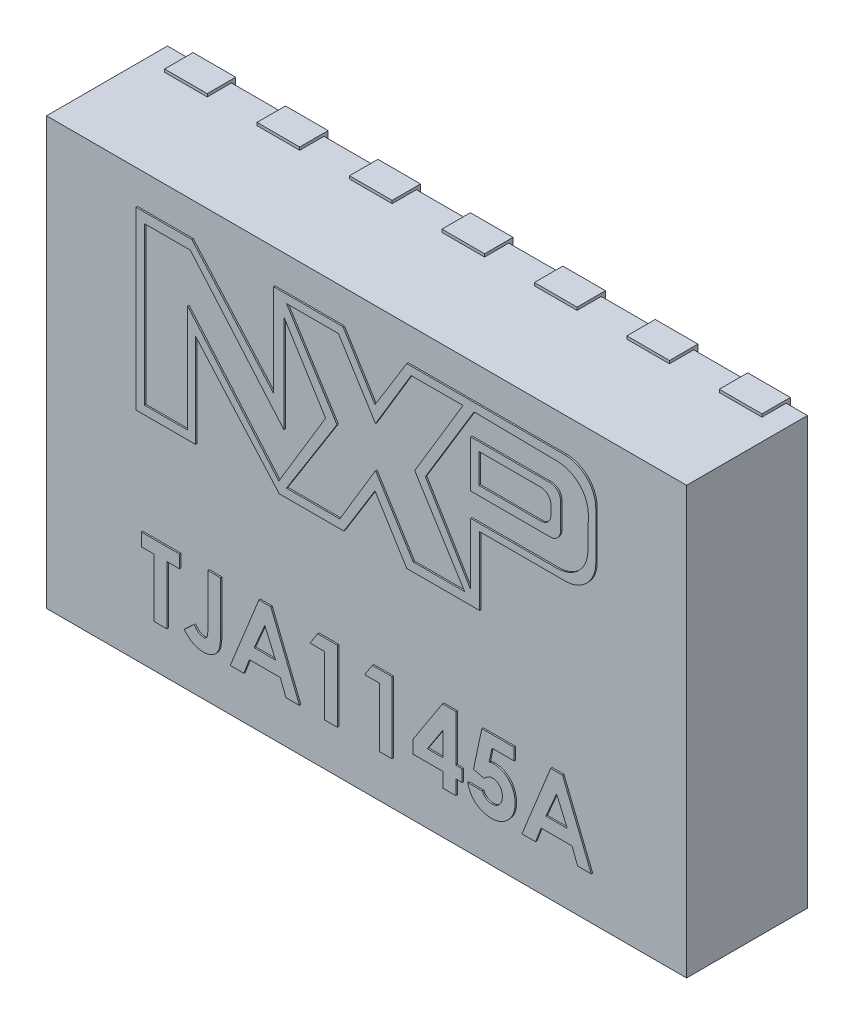
SolidWorks part; units mm, degrees
ref_plane "Front Plane" through (0, 0, 0) normal (0, 0, 1) x (1, 0, 0)
ref_plane "Top Plane" through (0, 0, 0) normal (0, 1, 0) x (1, 0, 0)
ref_plane "Right Plane" through (0, 0, 0) normal (1, 0, 0) x (0, 0, -1)
sketch "Sketch1" plane through (0, 0, 0) normal (0, 0, 1) x (1, 0, 0)
  line L1 (2.25, 1.5) -> (-2.25, 1.5)
  line L2 (2.25, 1.5) -> (2.25, -1.5)
  line L3 (2.25, -1.5) -> (-2.25, -1.5)
  line L4 (-2.25, 1.5) -> (-2.25, -1.5)
  line L5 (2.25, 1.5) -> (-2.25, -1.5) construction
  line L6 (2.25, -1.5) -> (-2.25, 1.5) construction
  point P0 (0, 0)
  dimension "D1" = 4.5
  dimension "D2" = 3
extrude "Boss-Extrude1" add sketch "Sketch1" along normal blind 0.85
sketch "Sketch2" plane through (0, 0, 0) normal (0, 0, -1) x (-1, 0, 0)
  line L0 (-2.25, 1.5) -> (2.25, 1.5) construction
  line L1 (2.1, 0.8) -> (-2.1, 0.8)
  line L2 (2.1, 0.8) -> (2.1, -0.8)
  line L3 (2.1, -0.8) -> (-2.1, -0.8)
  line L4 (-2.1, 0.8) -> (-2.1, -0.8)
  line L5 (2.1, 0.8) -> (-2.1, -0.8) construction
  line L6 (2.1, -0.8) -> (-2.1, 0.8) construction
  line L7 (-2.1, 1.6573) -> (-1.8, 1.6573)
  line L8 (-2.1, 1.6573) -> (-2.1, 1.1)
  line L9 (-2.1, 1.1) -> (-1.8, 1.1)
  line L10 (-1.8, 1.6573) -> (-1.8, 1.1)
  line L11 (-1.45, 1.6573) -> (-1.45, 1.1)
  line L12 (-1.45, 1.6573) -> (-1.15, 1.6573)
  line L13 (-1.15, 1.6573) -> (-1.15, 1.1)
  line L14 (-1.45, 1.1) -> (-1.15, 1.1)
  line L15 (-0.8, 1.6573) -> (-0.8, 1.1)
  line L16 (-0.8, 1.6573) -> (-0.5, 1.6573)
  line L17 (-0.5, 1.6573) -> (-0.5, 1.1)
  line L18 (-0.8, 1.1) -> (-0.5, 1.1)
  line L19 (-0.15, 1.6573) -> (-0.15, 1.1)
  line L20 (-0.15, 1.6573) -> (0.15, 1.6573)
  line L21 (0.15, 1.6573) -> (0.15, 1.1)
  line L22 (-0.15, 1.1) -> (0.15, 1.1)
  line L23 (0.5, 1.6573) -> (0.5, 1.1)
  line L24 (0.5, 1.6573) -> (0.8, 1.6573)
  line L25 (0.8, 1.6573) -> (0.8, 1.1)
  line L26 (0.5, 1.1) -> (0.8, 1.1)
  line L27 (1.15, 1.6573) -> (1.15, 1.1)
  line L28 (1.15, 1.6573) -> (1.45, 1.6573)
  line L29 (1.45, 1.6573) -> (1.45, 1.1)
  line L30 (1.15, 1.1) -> (1.45, 1.1)
  line L31 (1.8, 1.6573) -> (1.8, 1.1)
  line L32 (1.8, 1.6573) -> (2.1, 1.6573)
  line L33 (2.1, 1.6573) -> (2.1, 1.1)
  line L34 (1.8, 1.1) -> (2.1, 1.1)
  line L35 (0, 0) -> (1.2289, 0) construction
  line L36 (1.8, -1.1) -> (2.1, -1.1)
  line L37 (2.1, -1.6573) -> (2.1, -1.1)
  line L38 (1.8, -1.6573) -> (2.1, -1.6573)
  line L39 (1.8, -1.6573) -> (1.8, -1.1)
  line L40 (1.15, -1.1) -> (1.45, -1.1)
  line L41 (1.45, -1.6573) -> (1.45, -1.1)
  line L42 (1.15, -1.6573) -> (1.45, -1.6573)
  line L43 (1.15, -1.6573) -> (1.15, -1.1)
  line L44 (0.5, -1.1) -> (0.8, -1.1)
  line L45 (0.8, -1.6573) -> (0.8, -1.1)
  line L46 (0.5, -1.6573) -> (0.8, -1.6573)
  line L47 (0.5, -1.6573) -> (0.5, -1.1)
  line L48 (-0.15, -1.1) -> (0.15, -1.1)
  line L49 (0.15, -1.6573) -> (0.15, -1.1)
  line L50 (-0.15, -1.6573) -> (0.15, -1.6573)
  line L51 (-0.15, -1.6573) -> (-0.15, -1.1)
  line L52 (-0.8, -1.1) -> (-0.5, -1.1)
  line L53 (-0.5, -1.6573) -> (-0.5, -1.1)
  line L54 (-0.8, -1.6573) -> (-0.5, -1.6573)
  line L55 (-0.8, -1.6573) -> (-0.8, -1.1)
  line L56 (-1.45, -1.1) -> (-1.15, -1.1)
  line L57 (-1.15, -1.6573) -> (-1.15, -1.1)
  line L58 (-1.45, -1.6573) -> (-1.15, -1.6573)
  line L59 (-1.45, -1.6573) -> (-1.45, -1.1)
  line L60 (-1.8, -1.6573) -> (-1.8, -1.1)
  line L61 (-2.1, -1.1) -> (-1.8, -1.1)
  line L62 (-2.1, -1.6573) -> (-2.1, -1.1)
  line L63 (-2.1, -1.6573) -> (-1.8, -1.6573)
  point P0 (0, 0)
  dimension "D1" = 1.6
  dimension "D2" = 4.2
  dimension "D3" = 0.4
  dimension "D4" = 0.3
  dimension "D5" = 7
extrude "Boss-Extrude2" add sketch "Sketch2" along normal blind 0.03
sketch "Sketch3" plane through (0, 0, 0.85) normal (0, 0, 1) x (1, 0, 0)
  line L1 (-2.25, 1.5) -> (3.2924, 1.5)
  line L2 (-2.25, 1.5) -> (-2.25, 1.9025)
  line L3 (-2.25, 1.9025) -> (3.2924, 1.9025)
  line L4 (3.2924, 1.5) -> (3.2924, 1.9025)
  line L5 (-2.25, -1.5) -> (2.8586, -1.5)
  line L6 (-2.25, -1.5) -> (-2.25, -2.0374)
  line L7 (-2.25, -2.0374) -> (2.8586, -2.0374)
  line L8 (2.8586, -1.5) -> (2.8586, -2.0374)
extrude "Cut-Extrude1" cut sketch "Sketch3" against normal blind 2.03
sketch "Sketch4" plane through (0, -1.5, 0) normal (0, -1, 0) x (1, 0, 0)
  line L0 (-1.8, 0) -> (-1.8, -0.03) construction
  line L1 (-2.1, -0.03) -> (-1.8, -0.03)
  line L2 (-2.1, -0.03) -> (-2.1, 0.17)
  line L3 (-2.1, 0.17) -> (-1.8, 0.17)
  line L4 (-1.8, -0.03) -> (-1.8, 0.17)
  line L5 (-1.45, -0.03) -> (-1.45, 0.17)
  line L6 (-1.45, -0.03) -> (-1.15, -0.03)
  line L7 (-1.15, -0.03) -> (-1.15, 0.17)
  line L8 (-1.45, 0.17) -> (-1.15, 0.17)
  line L9 (-0.8, -0.03) -> (-0.8, 0.17)
  line L10 (-0.8, -0.03) -> (-0.5, -0.03)
  line L11 (-0.5, -0.03) -> (-0.5, 0.17)
  line L12 (-0.8, 0.17) -> (-0.5, 0.17)
  line L13 (-0.15, -0.03) -> (-0.15, 0.17)
  line L14 (-0.15, -0.03) -> (0.15, -0.03)
  line L15 (0.15, -0.03) -> (0.15, 0.17)
  line L16 (-0.15, 0.17) -> (0.15, 0.17)
  line L17 (0.5, -0.03) -> (0.5, 0.17)
  line L18 (0.5, -0.03) -> (0.8, -0.03)
  line L19 (0.8, -0.03) -> (0.8, 0.17)
  line L20 (0.5, 0.17) -> (0.8, 0.17)
  line L21 (1.15, -0.03) -> (1.15, 0.17)
  line L22 (1.15, -0.03) -> (1.45, -0.03)
  line L23 (1.45, -0.03) -> (1.45, 0.17)
  line L24 (1.15, 0.17) -> (1.45, 0.17)
  line L25 (1.8, -0.03) -> (1.8, 0.17)
  line L26 (1.8, -0.03) -> (2.1, -0.03)
  line L27 (2.1, -0.03) -> (2.1, 0.17)
  line L28 (1.8, 0.17) -> (2.1, 0.17)
  dimension "D1" = 0
  dimension "D2" = 0.2
  dimension "D3" = 7
extrude "Boss-Extrude3" add sketch "Sketch4" along normal blind 0.02
mirror "Mirror1" about plane through (0, 0, 0) normal (0, 1, 0) of "Boss-Extrude3"
sketch "Sketch8" plane through (0, 0, 0.85) normal (0, 0, 1) x (1, 0, 0)
  line L0 (70.666, 256.4211) -> (518.666, 256.4211) construction
  line L1 (-1.2186, 1.2679) -> (-0.6447, 0.6189)
  line L2 (-0.5532, 1.2103) -> (-0.188, 1.2103)
  line L3 (0.6998, 0.0824) -> (0.3376, 0.0824)
  line L4 (-0.6447, 1.2679) -> (-0.1555, 1.2679)
  line L5 (-1.1921, 0.6918) -> (-1.1921, 0.0329)
  line L6 (-0.188, 1.2103) -> (0.0731, 0.7923)
  line L7 (-0.1497, 0.0266) -> (-0.6039, 0.0266)
  line L8 (-1.1921, 0.0329) -> (-1.6111, 0.0329)
  line L9 (0.7662, 1.2103) -> (1.3564, 1.202)
  line L10 (0.742, 1.046) -> (0.742, 0.7163)
  line L11 (1.4057, 0.5003) -> (0.8054, 0.5003)
  line L12 (-1.552, 0.0924) -> (-1.552, 1.1975)
  line L13 (0.7998, 0.9863) -> (1.2343, 0.9863)
  line L14 (1.5693, 0.983) -> (1.5662, 0.7627)
  line L15 (1.3063, 0.9143) -> (1.3063, 0.852)
  line L16 (-1.6111, 0.0329) -> (-1.6111, 1.2679)
  line L17 (0.8054, 0.0202) -> (0.293, 0.0202)
  line L18 (-0.1981, 0.65) -> (-0.5532, 1.2103)
  line L19 (0.742, 0.5497) -> (0.742, 0.1156)
  line L20 (0.293, 1.2679) -> (1.4057, 1.2679)
  line L21 (-0.5714, 0.4334) -> (-0.5714, 1.1203)
  line L22 (0.3488, 0.6442) -> (0.6998, 0.0824)
  line L23 (0.293, 0.0202) -> (0.0692, 0.381)
  line L24 (-0.6069, 0.1027) -> (-1.248, 0.8474)
  line L25 (0.4233, 0.6442) -> (0.7662, 1.2103)
  line L26 (1.3016, 0.7163) -> (0.742, 0.7163)
  line L27 (1.6217, 1.0519) -> (1.6217, 0.7163)
  line L28 (-0.6039, 0.0266) -> (-1.1921, 0.6918)
  line L29 (0.0731, 0.5059) -> (-0.1786, 0.086)
  line L30 (0.0692, 0.9056) -> (0.293, 1.2679)
  line L31 (0.0731, 0.7923) -> (0.3236, 1.2103)
  line L32 (-0.5532, 0.086) -> (-0.1981, 0.65)
  line L33 (-0.5714, 1.1203) -> (-0.278, 0.65)
  line L34 (0.3236, 1.2103) -> (0.6882, 1.2103)
  line L35 (0.7998, 0.9863) -> (0.7998, 0.78)
  line L36 (-0.1786, 0.086) -> (-0.5532, 0.086)
  line L37 (0.7998, 0.78) -> (1.2343, 0.78)
  line L38 (0.3376, 0.0824) -> (0.0731, 0.5059)
  line L39 (0.742, 1.046) -> (1.3016, 1.046)
  line L40 (0.8054, 0.5003) -> (0.8054, 0.0202)
  line L41 (-1.2291, 1.1975) -> (-0.5714, 0.4334)
  line L42 (1.3736, 0.974) -> (1.3736, 0.7883)
  line L43 (-0.1555, 1.2679) -> (0.0692, 0.9056)
  line L44 (0.0692, 0.381) -> (-0.1497, 0.0266)
  line L45 (-1.248, 0.0924) -> (-1.552, 0.0924)
  line L46 (1.3503, 0.5497) -> (0.742, 0.5497)
  line L47 (-1.6111, 1.2679) -> (-1.2186, 1.2679)
  line L48 (-0.278, 0.65) -> (-0.6069, 0.1027)
  line L49 (0.6882, 1.2103) -> (0.3488, 0.6442)
  line L50 (-0.6447, 0.6189) -> (-0.6447, 1.2679)
  line L51 (-1.552, 1.1975) -> (-1.2291, 1.1975)
  line L52 (-1.248, 0.8474) -> (-1.248, 0.0924)
  line L53 (0.742, 0.1156) -> (0.4233, 0.6442)
  line L54 (-1.6111, -1.125) -> (1.3503, -1.125) construction
  arc A0 (1.3016, 1.046) -> (1.3736, 0.974) centre (1.3016, 0.974) cw
  arc A1 (1.4057, 1.2679) -> (1.6217, 1.0519) centre (1.4057, 1.0519) cw
  arc A2 (1.3736, 0.7883) -> (1.3016, 0.7163) centre (1.3016, 0.7883) cw
  arc A3 (1.6217, 0.7163) -> (1.4057, 0.5003) centre (1.4057, 0.7163) cw
  arc A4 (1.2343, 0.9863) -> (1.3063, 0.9143) centre (1.2343, 0.9143) cw
  arc A5 (1.5662, 0.7627) -> (1.3503, 0.5497) centre (1.3503, 0.7657) cw
  arc A6 (1.2343, 0.78) -> (1.3063, 0.852) centre (1.2343, 0.852) ccw
  arc A7 (1.3564, 1.202) -> (1.5693, 0.983) centre (1.3533, 0.9861) cw
  text T0 "<b>TJA1145A</b>" font "Century Gothic" height 0.5
extrude "Boss-Extrude4" add sketch "Sketch8" along normal blind 0.01 contours A3 L27 A1 L20 L30 L43 L4 L50 L1 L47 L16 L8 L5 L28 L7 L44 L23 L17 L40 L11 L34 L49 L22 L3 L38 L29 L36 L32 L18 L2 L6 L31 L24 L52 L45 L12 L51 L41 L21 L33 L48 L9 A7 L14 A5 L46 L19 L53 | A2 L42 A0 L39 L10 L26 A6 L37 L35 L13 A4 L15
sketch "Sketch9" plane through (0, 0, 0.85) normal (0, 0, 1) x (1, 0, 0)
  line L0 (-1.58, -1.1911) -> (1.6601, -1.1911) construction
  text T0 "<b>TJA1145A</b>" font "Century Gothic" height 0.5
  point P3 (-1.5348, -1.1911)
  point P4 (-1.58, -1.1911)
extrude "Boss-Extrude5" add sketch "Sketch9" along normal blind 0.01
